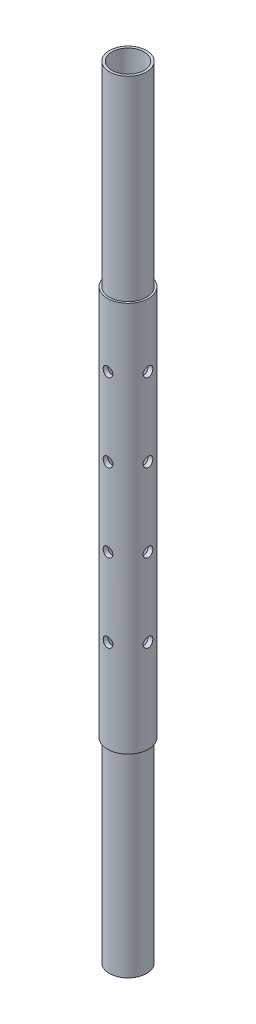
SolidWorks part; units mm, degrees
ref_plane "Front Plane" through (0, 0, 0) normal (0, 0, 1) x (1, 0, 0)
ref_plane "Top Plane" through (0, 0, 0) normal (0, 1, 0) x (1, 0, 0)
ref_plane "Right Plane" through (0, 0, 0) normal (1, 0, 0) x (0, 0, -1)
sketch "Sketch1" plane through (0, 0, 0) normal (0, 1, 0) x (1, 0, 0)
  circle A0 centre (0, 0) radius 13.335
  circle A1 centre (0, 0) radius 10.4648
  dimension "D1" = 26.67
  dimension "D2" = 2.8702
extrude "Boss-Extrude1" add sketch "Sketch1" along normal mid plane 508
sketch "Sketch2" plane through (0, 0, 0) normal (0, 0, 1) x (1, 0, 0)
  line L0 (-178.095, 0) -> (178.095, 0) construction
  line L1 (0, -321.7876) -> (0, 321.7876) construction
  line L2 (-62.2592, -152.4) -> (62.2592, -152.4) construction
  line L3 (-62.2592, -66.675) -> (62.2592, -66.675) construction
  line L4 (-65.9857, -15.875) -> (65.9857, -15.875) construction
  line L5 (-78.4073, 34.925) -> (78.4073, 34.925) construction
  line L6 (-13.335, -254) -> (13.335, -254) construction
  line L7 (-75.6739, 85.725) -> (75.6739, 85.725) construction
  line L8 (-88.1047, 149.225) -> (88.1047, 149.225) construction
  line L9 (-129.0131, 250.825) -> (129.0131, 250.825) construction
  circle A0 centre (0, -66.675) radius 3.175
  circle A1 centre (0, -15.875) radius 3.175
  circle A2 centre (0, 34.925) radius 3.175
  circle A3 centre (0, 85.725) radius 3.175
  point P4 (0, 0)
  point P8 (0, 0)
  point P11 (0, -152.4)
  point P14 (0, -66.675)
  point P17 (0, -15.875)
  point P20 (0, 34.925)
  point P25 (0, 85.725)
  point P28 (0, 149.225)
  point P31 (0, 250.825)
  dimension "D8" = 6.35
  dimension "D1" = 101.6
  dimension "D2" = 85.725
  dimension "D3" = 50.8
  dimension "D4" = 50.8
  dimension "D5" = 50.8
  dimension "D6" = 63.5
  dimension "D7" = 101.6
  dimension "D9" = 4
extrude "Cut-Extrude1" cut sketch "Sketch2" against normal mid plane 127
sketch "Sketch3" plane through (0, 0, 0) normal (1, 0, 0) x (0, 0, -1)
  line L0 (-192.9623, 0) -> (192.9623, 0) construction
  line L1 (0, -277.3935) -> (0, 277.3935) construction
  line L2 (-89.6837, -152.4) -> (89.6837, -152.4) construction
  line L3 (-98.4488, -66.675) -> (98.4488, -66.675) construction
  line L4 (-71.49, 149.225) -> (71.49, 149.225) construction
  line L5 (-98.4488, -15.875) -> (98.4488, -15.875) construction
  line L6 (-98.4488, 34.925) -> (98.4488, 34.925) construction
  line L7 (-98.4488, 85.725) -> (98.4488, 85.725) construction
  line L8 (-13.335, -254) -> (13.335, -254) construction
  line L9 (-71.49, 250.825) -> (71.49, 250.825) construction
  circle A0 centre (0, -66.675) radius 3.175
  circle A1 centre (0, -15.875) radius 3.175
  circle A2 centre (0, 34.925) radius 3.175
  circle A3 centre (0, 85.725) radius 3.175
  point P4 (0, 0)
  point P8 (0, 0)
  point P11 (0, -152.4)
  point P14 (0, -66.675)
  point P17 (0, -76.5821)
  point P20 (0, -15.875)
  point P23 (0, 34.925)
  point P26 (0, 85.725)
  point P28 (0, 149.225)
  point P31 (0, 250.825)
  dimension "D8" = 6.35
  dimension "D1" = 101.6
  dimension "D2" = 85.725
  dimension "D3" = 50.8
  dimension "D4" = 50.8
  dimension "D5" = 50.8
  dimension "D6" = 63.5
  dimension "D7" = 101.6
  dimension "D9" = 4
extrude "Cut-Extrude2" cut sketch "Sketch3" against normal mid plane 127
sketch "Sketch4" plane through (0, 254, 0) normal (0, 1, 0) x (1, 0, 0)
  line L0 (-46.3542, 0) -> (46.3542, 0) construction
  line L1 (0, -42.7267) -> (0, 42.7267) construction
  circle A0 centre (0, 0) radius 12.065
  circle A1 centre (0, 0) radius 13.335
  point P6 (0, 0)
  point P10 (0, 0)
  dimension "D1" = 24.13
extrude "Cut-Extrude3" cut sketch "Sketch4" against normal blind 127
sketch "Sketch5" plane through (0, -254, 0) normal (0, -1, 0) x (1, 0, 0)
  line L0 (-23.9177, 0) -> (23.9177, 0) construction
  line L1 (0, -20.7348) -> (0, 20.7348) construction
  circle A0 centre (0, 0) radius 12.065
  circle A1 centre (0, 0) radius 13.335
  point P5 (0, 0)
  point P6 (0, 0)
  point P9 (0, 0)
  dimension "D1" = 24.13
extrude "Cut-Extrude4" cut sketch "Sketch5" against normal blind 127
